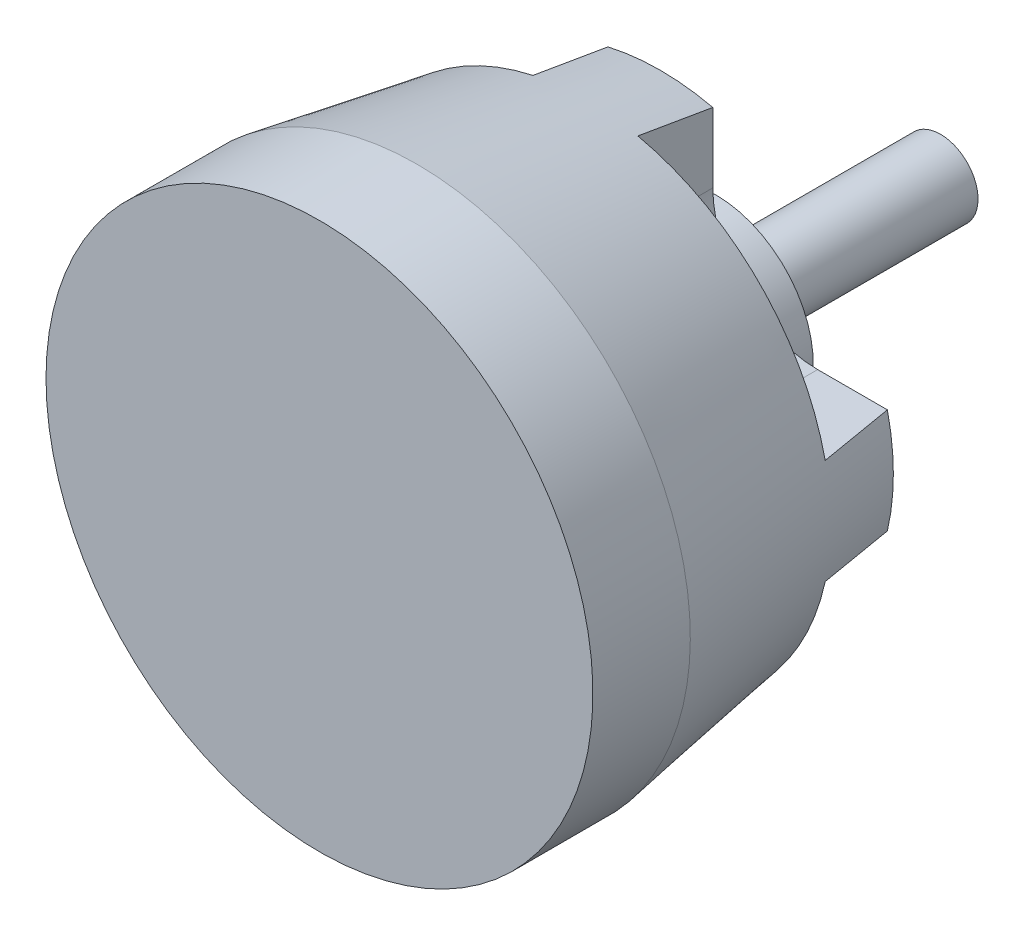
SolidWorks part; units mm, degrees
ref_plane "Front Plane" through (0, 0, 0) normal (0, 0, 1) x (1, 0, 0)
ref_plane "Top Plane" through (0, 0, 0) normal (0, 1, 0) x (1, 0, 0)
ref_plane "Right Plane" through (0, 0, 0) normal (1, 0, 0) x (0, 0, -1)
sketch "Sketch1" plane through (0, 0, 0) normal (0, 0, 1) x (1, 0, 0)
  circle A0 centre (0, 0) radius 18.25
  dimension "D1" = 36.5
extrude "Boss-Extrude1" add sketch "Sketch1" along normal blind 6.5
sketch "Sketch3" plane through (0, 0, 0) normal (1, 0, 0) x (0, 0, -1)
  line L0 (0, 18.25) -> (16.25, 15.55)
  line L1 (16.25, 15.55) -> (16.25, 0)
  line L2 (16.25, 0) -> (0, 0)
  line L3 (0, 18.25) -> (0, 0)
  dimension "D1" = 16.25
  dimension "D2" = 15.55
revolve "Revolve1" add sketch "Sketch3" angle 360 about L2
sketch "Sketch4" plane through (0, 0, -16.25) normal (0, 0, -1) x (-1, 0, 0)
  circle A0 centre (0, 0) radius 6.5
  dimension "D1" = 13
extrude "Boss-Extrude2" add sketch "Sketch4" along normal blind 3.7
sketch "Sketch5" plane through (0, 0, -19.95) normal (0, 0, -1) x (-1, 0, 0)
  circle A0 centre (0, 0) radius 2.5
  dimension "D1" = 5
extrude "Boss-Extrude3" add sketch "Sketch5" along normal blind 15
sketch "Sketch6" plane through (0, 0, -16.25) normal (0, 0, -1) x (-1, 0, 0)
  line L0 (-3.5, 15.151) -> (-3.5, 10.5)
  line L1 (3.5, 15.151) -> (3.5, 10.5)
  line L2 (-15.151, 3.5) -> (-10.5, 3.5)
  line L3 (15.151, -3.5) -> (10.5, -3.5)
  line L4 (10.5, 3.5) -> (15.151, 3.5)
  line L5 (-10.5, -3.5) -> (-15.151, -3.5)
  line L6 (-3.5, -10.5) -> (-3.5, -15.151)
  line L7 (3.5, -10.5) -> (3.5, -15.151)
  line L8 (3.5, 15.151) -> (3.5, 22.2569)
  line L9 (15.151, 3.5) -> (25.5981, 3.5)
  line L10 (25.5981, 3.5) -> (25.5981, 22.2569)
  line L11 (25.5981, 22.2569) -> (3.5, 22.2569)
  line L12 (-3.5, 15.151) -> (-3.5, 22.2569)
  line L13 (-3.5, 22.2569) -> (-21.4087, 22.2569)
  line L14 (-21.4087, 22.2569) -> (-21.4087, 3.5)
  line L15 (-21.4087, 3.5) -> (-15.151, 3.5)
  line L16 (-15.151, -3.5) -> (-25.9194, -3.5)
  line L17 (-25.9194, -3.5) -> (-25.9194, -21.5074)
  line L18 (-25.9194, -21.5074) -> (-3.5, -21.5074)
  line L19 (-3.5, -21.5074) -> (-3.5, -15.151)
  line L20 (3.5, -15.151) -> (3.5, -21.5074)
  line L21 (3.5, -21.5074) -> (25.5981, -21.5074)
  line L22 (25.5981, -21.5074) -> (25.5981, -3.5)
  line L23 (25.5981, -3.5) -> (15.151, -3.5)
  circle A0 centre (0, 0) radius 15.55 construction
  arc A1 (-10.5, -3.5) -> (-3.5, -10.5) centre (-10.5, -10.5) cw
  arc A2 (3.5, -10.5) -> (10.5, -3.5) centre (10.5, -10.5) cw
  arc A3 (10.5, 3.5) -> (3.5, 10.5) centre (10.5, 10.5) cw
  arc A4 (-10.5, 3.5) -> (-3.5, 10.5) centre (-10.5, 10.5) ccw
  point P16 (-3.5, -3.5)
  point P19 (3.5, -3.5)
  dimension "D3" = 7
  dimension "D1" = 7
  dimension "D2" = 7
extrude "Cut-Extrude1" cut sketch "Sketch6" against normal blind 5
sketch "Sketch7" plane through (0, 0, -16.25) normal (0, 0, -1) x (-1, 0, 0)
  circle A0 centre (0, 0) radius 12.5 construction
  circle A1 centre (0, 12.5) radius 1.5
  circle A2 centre (12.5, 0) radius 1.5
  circle A3 centre (-12.5, 0) radius 1.5
  circle A4 centre (0, -12.5) radius 1.5
  dimension "D1" = 25
  dimension "D2" = 3
extrude "Cut-Extrude2" cut sketch "Sketch7" against normal blind 6
